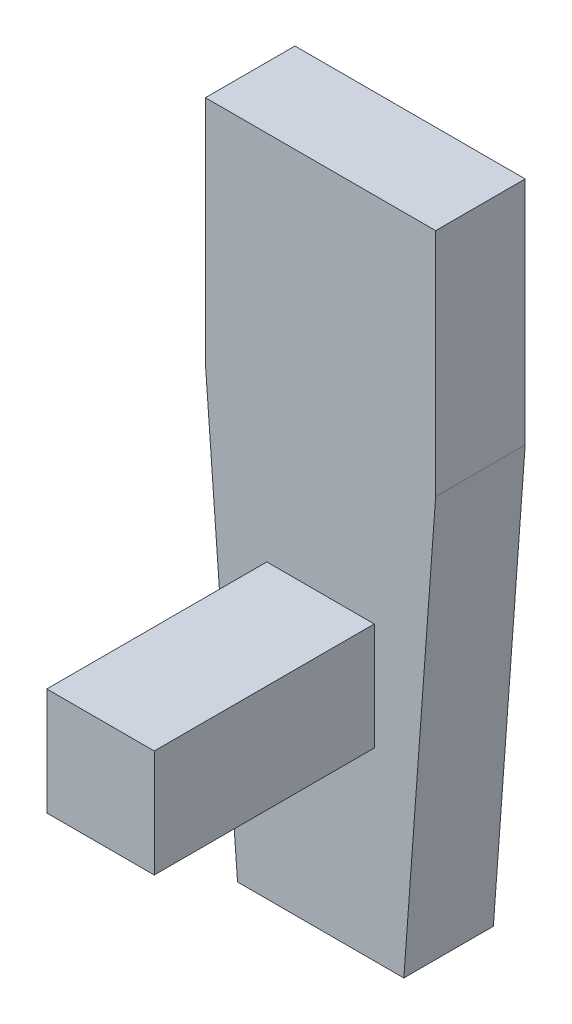
SolidWorks part; units mm, degrees
ref_plane "Ebene vorne" through (0, 0, 0) normal (0, 0, 1) x (1, 0, 0)
ref_plane "Ebene oben" through (0, 0, 0) normal (0, 1, 0) x (1, 0, 0)
ref_plane "Ebene rechts" through (0, 0, 0) normal (1, 0, 0) x (0, 0, -1)
sketch "Skizze1" plane through (0, 0, 0) normal (0, 0, 1) x (1, 0, 0)
  line L0 (-32.4449, -45.5269) -> (-45, 123.701)
  line L1 (0, 168.701) -> (0, 0) construction
  line L2 (-32.4449, -45.5269) -> (32.5551, -45.5269)
  line L3 (-32.4449, -45.5269) -> (-32.4449, 19.4731)
  line L4 (-45, 123.701) -> (45, 123.701)
  line L5 (-45, 123.701) -> (-45, 213.701)
  line L6 (-45, 213.701) -> (45, 213.701)
  line L7 (45, 123.701) -> (45, 213.701)
  line L8 (-45, 123.701) -> (45, 213.701) construction
  line L9 (-45, 213.701) -> (45, 123.701) construction
  line L10 (-32.4449, 19.4731) -> (32.5551, 19.4731)
  line L11 (32.5551, -45.5269) -> (32.5551, 19.4731)
  line L12 (-32.4449, -45.5269) -> (32.5551, 19.4731) construction
  line L13 (-32.4449, 19.4731) -> (32.5551, -45.5269) construction
  line L14 (45, 123.701) -> (32.5551, -45.5269)
  circle A1 centre (0, 168.701) radius 45
  point P0 (0.0551, -13.0269)
  dimension "D1" = 65
  dimension "D2" = 90
  dimension "D3" = 65
extrude "Aufsatz-Linear austragen1" add sketch "Skizze1" along normal blind 35
sketch "Skizze2" plane through (0, 0, 35) normal (0, 0, 1) x (1, 0, 0)
  line L0 (0, 47.5491) -> (0, 0) construction
  line L2 (-21, 26.5491) -> (21, 26.5491)
  line L3 (-21, 26.5491) -> (-21, 68.5491)
  line L4 (-21, 68.5491) -> (21, 68.5491)
  line L5 (21, 26.5491) -> (21, 68.5491)
  line L6 (-21, 26.5491) -> (21, 68.5491) construction
  line L7 (-21, 68.5491) -> (21, 26.5491) construction
  point P7 (0.0004, 47.5491)
  dimension "D2" = 42
  dimension "D3" = 42
extrude "Aufsatz-Linear austragen2" add sketch "Skizze2" along normal blind 86
sketch "Skizze3" plane through (0, 0, 0) normal (0, 0, -1) x (-1, 0, 0)
  line L0 (-22.4876, 146.2009) -> (-22.0498, 67.4556)
  line L1 (-22.4876, 146.2009) -> (22.5124, 146.2009)
  line L2 (-22.4876, 146.2009) -> (-22.4876, 191.2009)
  line L3 (-22.4876, 191.2009) -> (22.5124, 191.2009)
  line L4 (22.5124, 146.2009) -> (22.5124, 191.2009)
  line L5 (-22.4876, 146.2009) -> (22.5124, 191.2009) construction
  line L6 (-22.4876, 191.2009) -> (22.5124, 146.2009) construction
  line L7 (-22.0498, 22.4556) -> (22.9502, 22.4556)
  line L8 (-22.0498, 22.4556) -> (-22.0498, 67.4556)
  line L9 (-22.0498, 67.4556) -> (22.9502, 67.4556)
  line L10 (22.9502, 22.4556) -> (22.9502, 67.4556)
  line L11 (-22.0498, 22.4556) -> (22.9502, 67.4556) construction
  line L12 (-22.0498, 67.4556) -> (22.9502, 22.4556) construction
  line L13 (22.9502, 67.4556) -> (22.5124, 146.2009)
  point P0 (0.4502, 44.9556)
  point P2 (0.0124, 168.7009)
  point P10 (0.0124, 168.7009)
  dimension "D1" = 45
  dimension "D2" = 45
  dimension "D3" = 45
extrude "Aufsatz-Linear austragen3" add sketch "Skizze3" along normal blind 15 contours L1 L4 L3 L2 | L9 L13 L1 L0 | L7 L10 L9 L8
